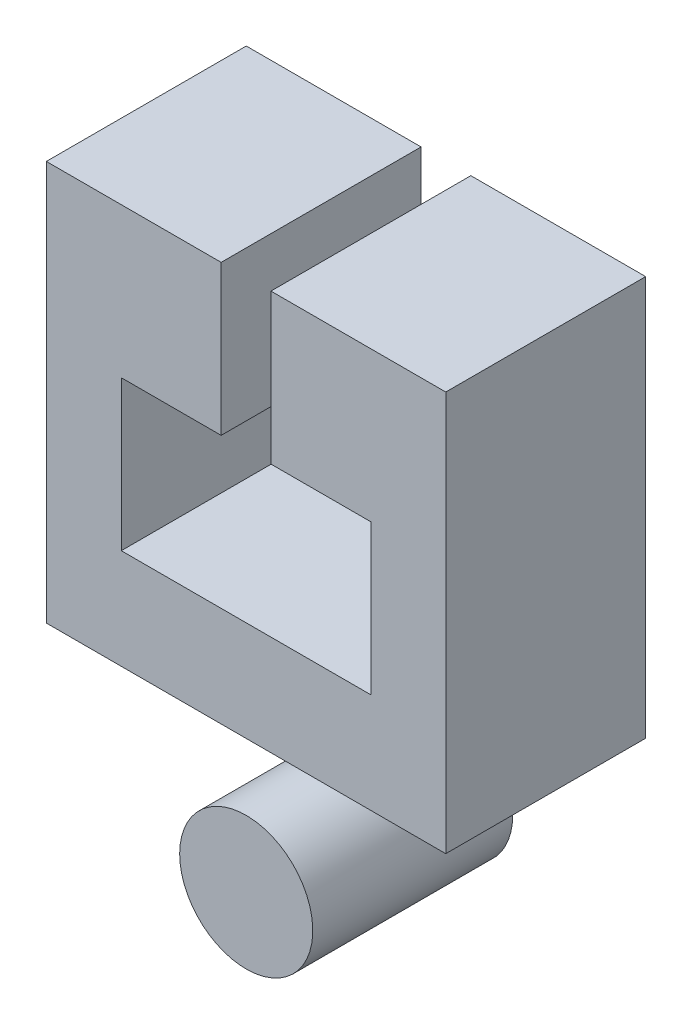
SolidWorks part; units mm, degrees
material "6061-T6 (SS)"
ref_plane "Front Plane" through (0, 0, 0) normal (0, 0, 1) x (1, 0, 0)
ref_plane "Top Plane" through (0, 0, 0) normal (0, 1, 0) x (1, 0, 0)
ref_plane "Right Plane" through (0, 0, 0) normal (1, 0, 0) x (0, 0, -1)
sketch "Sketch4" plane through (0, 0, 0) normal (0, 0, 1) x (1, 0, 0)
  line L0 (-50.7492, 0) -> (-50.7492, 101.6)
  line L1 (-50.7492, 0) -> (50.7492, 0)
  line L2 (0, 0) -> (0, 101.6)
  line L3 (-50.7492, 101.6) -> (50.7492, 101.6)
  line L4 (50.7492, 0) -> (50.7492, 101.6)
  dimension "D1" = 101.6
  dimension "D2" = 50.7492
extrude "Boss-Extrude2" add sketch "Sketch4" against normal blind 50.8 contours L3 L0 L1 L2 | L1 L4 L3 L2
sketch "Sketch5" plane through (0, 0, 0) normal (0, 0, 1) x (1, 0, 0)
  line L13 (-50.7492, 101.6) -> (50.7492, 101.6) construction
  line L14 (-6.3246, 101.6) -> (6.3246, 101.6)
  line L15 (6.3246, 101.6) -> (6.3246, 63.5254)
  line L16 (6.3246, 63.5254) -> (31.7043, 63.5254)
  line L17 (31.7043, 63.5254) -> (31.7043, 25.4508)
  line L18 (31.7043, 25.4508) -> (-31.7043, 25.4508)
  line L20 (-31.7043, 63.5254) -> (-31.7043, 25.4508)
  line L21 (-6.3246, 63.5254) -> (-31.7043, 63.5254)
  line L22 (-6.3246, 101.6) -> (-6.3246, 63.5254)
  dimension "D1" = 25.3797
  dimension "D2" = 12.6492
  dimension "D3" = 38.0746
extrude "Cut-Extrude2" cut sketch "Sketch5" against normal through all contours L15 L16 L17 L18 L20 L21 L22 L14
sketch "Sketch7" plane through (0, 0, -50.8) normal (0, 0, -1) x (-1, 0, 0)
  line L0 (-16.9598, -33.8328) -> (16.873, -33.8328)
  line L13 (50.7492, 0) -> (-50.7492, 0) construction
  line L14 (16.873, 0) -> (-16.9598, 0)
  line L15 (16.873, 0) -> (16.873, -33.8328)
  line L17 (-16.9598, 0) -> (-16.9598, -33.8328)
  dimension "D1" = 33.8328
  dimension "D2" = 33.8328
extrude "Boss-Extrude3" add sketch "Sketch7" against normal blind 0.5588
sketch "Sketch8" plane through (0, 0, -50.8) normal (0, 0, -1) x (-1, 0, 0)
  line L0 (-16.9598, -33.8328) -> (16.873, -33.8328) construction
  circle A0 centre (-0.0434, -33.8328) radius 16.9164
  dimension "D1" = 33.8328
extrude "Boss-Extrude4" add sketch "Sketch8" against normal blind 50.8
equation "\"in\"=6.75"
